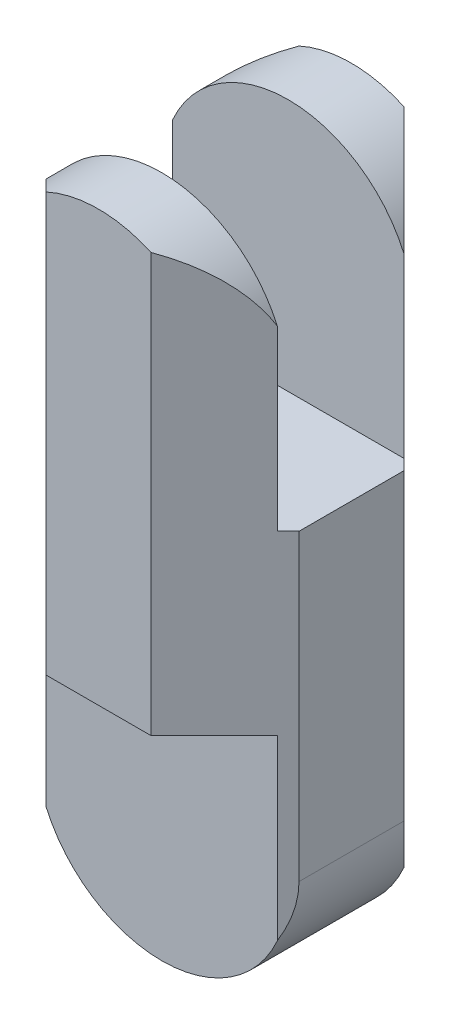
SolidWorks part; units mm, degrees
ref_plane "Front" through (0, 0, 0) normal (0, 0, 1) x (1, 0, 0)
ref_plane "Top" through (0, 0, 0) normal (0, 1, 0) x (1, 0, 0)
ref_plane "Right" through (0, 0, 0) normal (1, 0, 0) x (0, 0, -1)
sketch "草图1" plane through (0, 0, 0) normal (0, 1, 0) x (1, 0, 0)
  line L0 (-12.6518, 0) -> (13.462, 0) construction
  line L1 (0, 11.6722) -> (0, -14.1269) construction
  line L3 (10, 4.1421) -> (4.1421, 10)
  line L4 (4.1421, 10) -> (-4.1421, 10)
  line L5 (-4.1421, 10) -> (-10, 4.1421)
  line L6 (-10, 4.1421) -> (-10, -4.1421)
  line L7 (-10, -4.1421) -> (-4.1421, -10)
  line L8 (-4.1421, -10) -> (4.1421, -10)
  line L9 (4.1421, -10) -> (10, -4.1421)
  line L10 (10, -4.1421) -> (10, 4.1421)
  circle A0 centre (0, 0) radius 10 construction
extrude "凸台-拉伸1" add sketch "草图1" along normal blind 54
sketch "草图2" plane through (0, 0, 10) normal (0, 0, 1) x (1, 0, 0)
  line L0 (0, 0) -> (0, 24) construction
  line L7 (-10, 10) -> (-10, -2.3893)
  line L8 (-10, -2.3893) -> (10, -2.3893)
  line L9 (10, 10) -> (10, -2.3893)
  arc A1 (-10, 10) -> (10, 10) centre (0, 10) ccw
extrude "切除-拉伸1" cut sketch "草图2" against normal blind 66
sketch "草图4" plane through (0, 0, 10) normal (0, 0, 1) x (1, 0, 0)
  line L0 (10, 54) -> (10, 10) construction
  line L2 (-10, 10) -> (-10, 20)
  line L3 (-10, 20) -> (10, 20)
  line L4 (10, 10) -> (10, 20)
  arc A0 (-10, 10) -> (10, 10) centre (0, 10) ccw
extrude "切除-拉伸2" cut sketch "草图4" against normal blind 5
sketch "草图5" plane through (0, 0, -10) normal (0, 0, -1) x (-1, 0, 0)
  line L0 (10, 54) -> (10, 10) construction
  line L2 (-10, 10) -> (-10, 20)
  line L3 (-10, 20) -> (10, 20)
  line L4 (10, 10) -> (10, 20)
  arc A0 (-10, 10) -> (10, 10) centre (0, 10) ccw
extrude "切除-拉伸3" cut sketch "草图5" against normal blind 5
sketch "草图6" plane through (0, 0, 0) normal (0, 0, 1) x (1, 0, 0)
  line L0 (0, 54) -> (0, 0) construction
  line L1 (-4.1421, 54) -> (4.1421, 54) construction
  line L2 (10, 54) -> (10, 10) construction
  line L3 (-10, 54) -> (10, 54)
  line L4 (-10, 54) -> (-10, 34)
  line L5 (-10, 34) -> (10, 34)
  line L6 (10, 54) -> (10, 34)
  dimension "D1" = 20
extrude "切除-拉伸4" cut sketch "草图6" against normal mid plane 10
sketch "草图7" plane through (0, 0, 10) normal (0, 0, 1) x (1, 0, 0)
  line L0 (0, 54) -> (0, 0) construction
  line L1 (-4.1421, 54) -> (4.1421, 54) construction
  line L4 (-10, 44) -> (-10, 63.6612)
  line L5 (-10, 63.6612) -> (10, 63.6612)
  line L6 (10, 44) -> (10, 63.6612)
  arc A0 (10, 44) -> (-10, 44) centre (0, 44) ccw
  point P6 (0, 0)
  point P11 (0, 0)
  point P12 (0, 0)
extrude "切除-拉伸5" cut sketch "草图7" against normal blind 30
